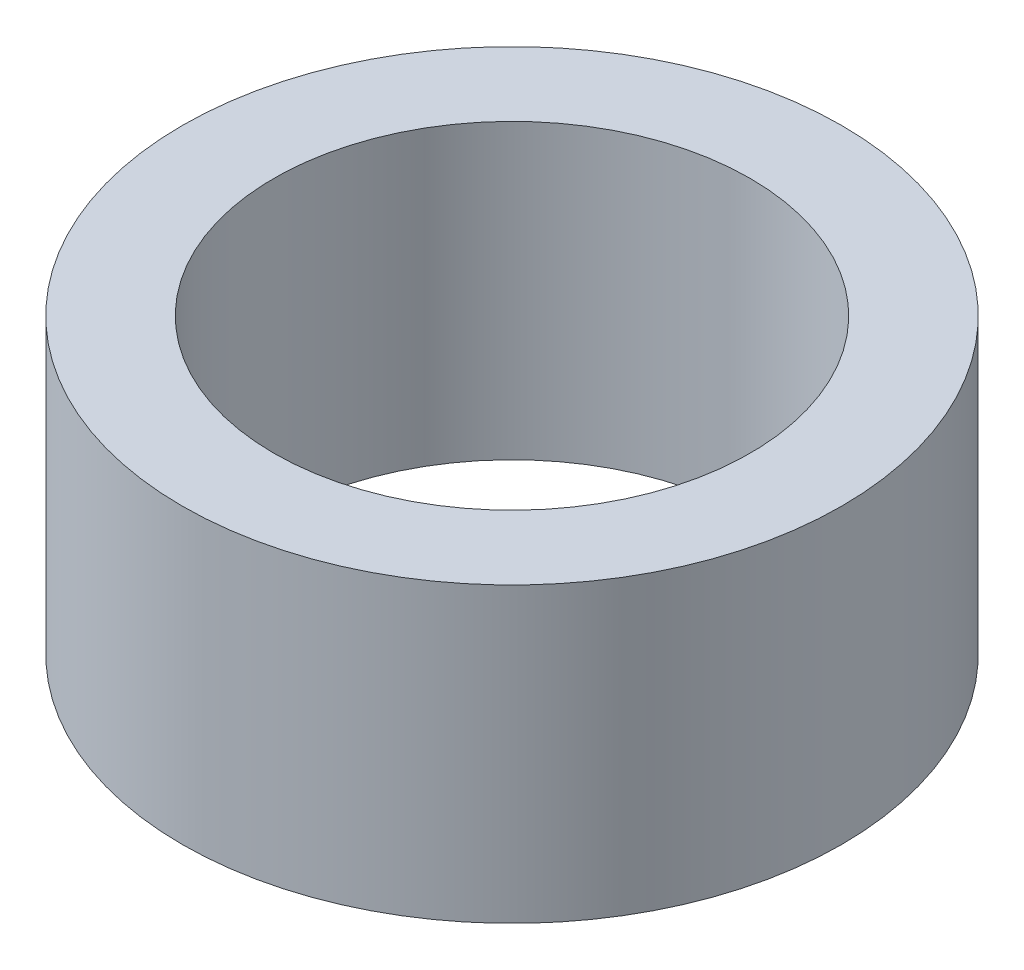
SolidWorks part; units mm, degrees
ref_plane "Front Plane" through (0, 0, 0) normal (0, 0, 1) x (1, 0, 0)
ref_plane "Top Plane" through (0, 0, 0) normal (0, 1, 0) x (1, 0, 0)
ref_plane "Right Plane" through (0, 0, 0) normal (1, 0, 0) x (0, 0, -1)
sketch "Sketch1" plane through (0, 0, 0) normal (0, 1, 0) x (1, 0, 0)
  circle A0 centre (0, 0) radius 6.5
  circle A1 centre (0, 0) radius 9
  dimension "D1" = 13
  dimension "D2" = 18
extrude "Boss-Extrude1" add sketch "Sketch1" along normal blind 8
